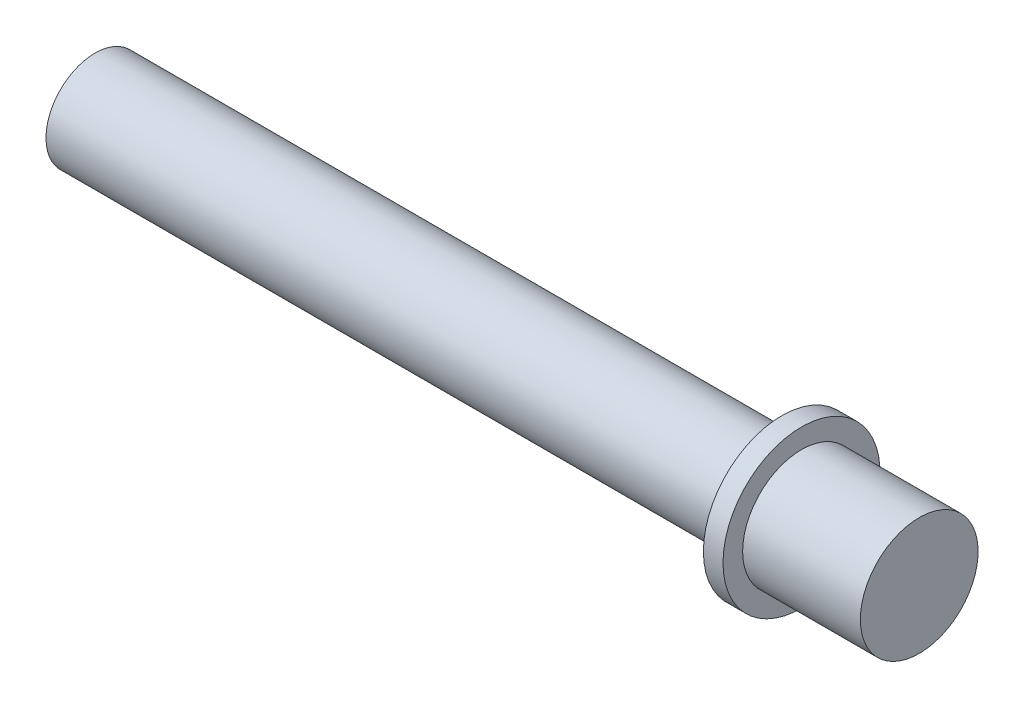
SolidWorks part; units mm, degrees
ref_plane "Front Plane" through (0, 0, 0) normal (0, 0, 1) x (1, 0, 0)
ref_plane "Top Plane" through (0, 0, 0) normal (0, 1, 0) x (1, 0, 0)
ref_plane "Right Plane" through (0, 0, 0) normal (1, 0, 0) x (0, 0, -1)
sketch "Sketch1" plane through (0, 0, 0) normal (0, 0, 1) x (1, 0, 0)
  line L0 (0, 0) -> (0, 6)
  line L1 (0, 6) -> (-12, 6)
  line L2 (-12, 6) -> (-12, 8)
  line L3 (-12, 8) -> (-14, 8)
  line L4 (-14, 8) -> (-14, 5)
  line L5 (-14, 5) -> (-84, 5)
  line L6 (-84, 5) -> (-84, 0)
  line L7 (-84, 0) -> (0, 0)
  dimension "D1" = 6
  dimension "D2" = 12
  dimension "D3" = 2
  dimension "D4" = 2
  dimension "D5" = 70
revolve "Revolve1" add sketch "Sketch1" angle 360 about L7
